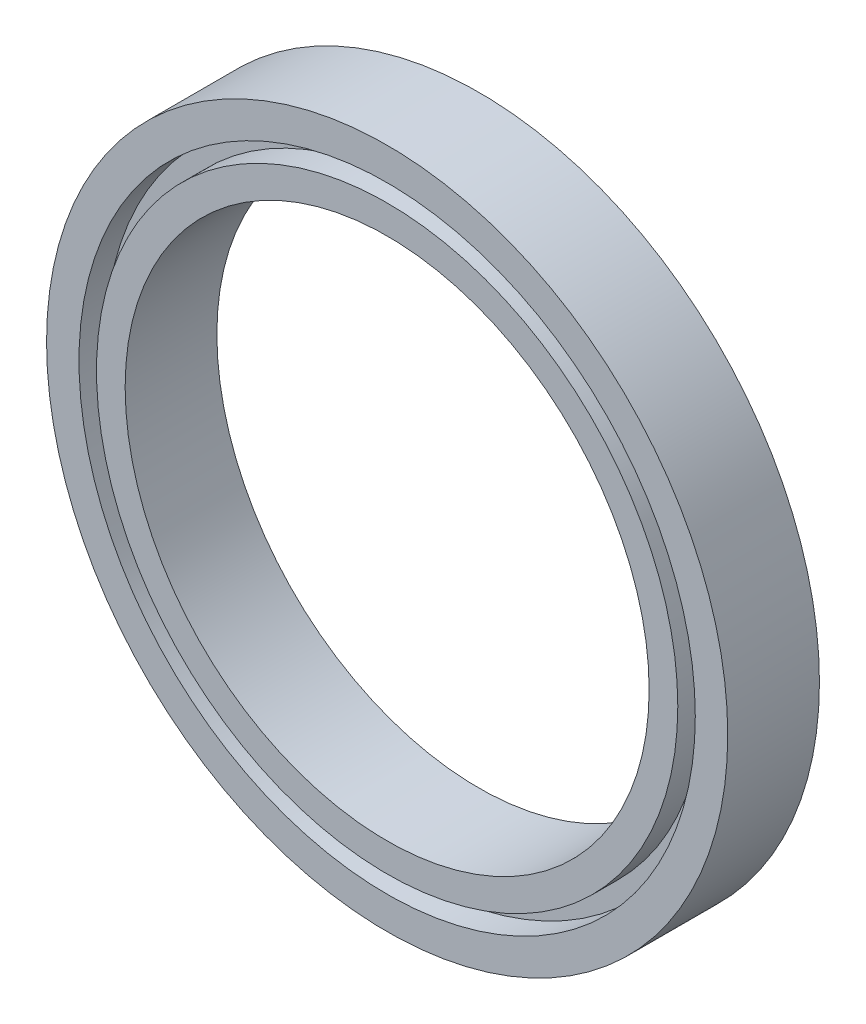
SolidWorks part; units mm, degrees
material "合金钢"
ref_plane "前视基准面" through (0, 0, 0) normal (0, 0, 1) x (1, 0, 0)
ref_plane "上视基准面" through (0, 0, 0) normal (0, 1, 0) x (1, 0, 0)
ref_plane "右视基准面" through (0, 0, 0) normal (1, 0, 0) x (0, 0, -1)
sketch "草图1" plane through (0, 0, 0) normal (0, 0, 1) x (1, 0, 0)
  circle A0 centre (0, 0) radius 26
  circle A1 centre (0, 0) radius 20
  dimension "D1" = 40
  dimension "D2" = 52
extrude "凸台-拉伸1" add sketch "草图1" along normal mid plane 7
sketch "草图2" plane through (0, 0, 3.5) normal (0, 0, 1) x (1, 0, 0)
  circle A0 centre (0, 0) radius 22.1871
  circle A1 centre (0, 0) radius 23.5233
extrude "切除-拉伸3" cut sketch "草图2" against normal blind 2
